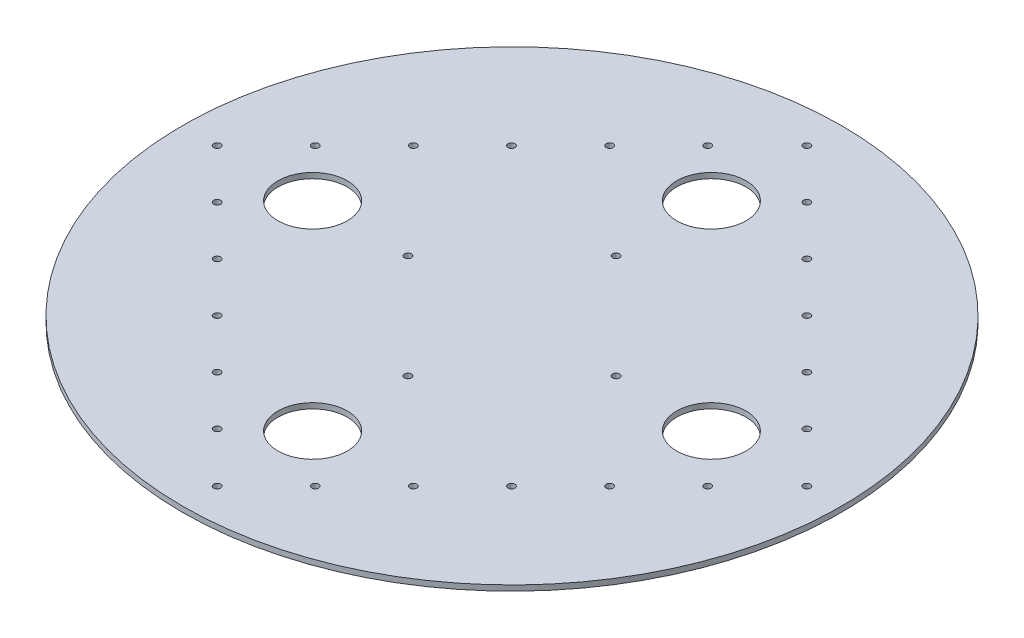
SolidWorks part; units mm, degrees
ref_plane "Front Plane" through (0, 0, 0) normal (0, 0, 1) x (1, 0, 0)
ref_plane "Top Plane" through (0, 0, 0) normal (0, 1, 0) x (1, 0, 0)
ref_plane "Right Plane" through (0, 0, 0) normal (1, 0, 0) x (0, 0, -1)
sketch "Sketch1" plane through (0, 0, 0) normal (0, 1, 0) x (1, 0, 0)
  line L0 (-170, 0) -> (0, 170) construction
  line L1 (-170, 0) -> (0, -170) construction
  circle A0 centre (0, 0) radius 190
  circle A1 centre (0, -170) radius 2
  circle A2 centre (-170, 0) radius 2
  circle A3 centre (0, 170) radius 2
  circle A4 centre (170, 0) radius 2
  circle A5 centre (-141.7157, 28.2843) radius 2
  circle A6 centre (-113.4315, 56.5685) radius 2
  circle A7 centre (-85.1472, 84.8528) radius 2
  circle A8 centre (-56.8629, 113.1371) radius 2
  circle A9 centre (-28.5786, 141.4214) radius 2
  circle A10 centre (-141.7157, -28.2843) radius 2
  circle A11 centre (28.2843, 141.7157) radius 2
  circle A12 centre (-113.4315, -56.5685) radius 2
  circle A13 centre (56.5685, 113.4315) radius 2
  circle A14 centre (-85.1472, -84.8528) radius 2
  circle A15 centre (84.8528, 85.1472) radius 2
  circle A16 centre (-56.8629, -113.1371) radius 2
  circle A17 centre (113.1371, 56.8629) radius 2
  circle A18 centre (-28.5786, -141.4214) radius 2
  circle A19 centre (141.4214, 28.5786) radius 2
  circle A20 centre (28.2843, -141.7157) radius 2
  circle A21 centre (56.5685, -113.4315) radius 2
  circle A22 centre (84.8528, -85.1472) radius 2
  circle A23 centre (113.1371, -56.8629) radius 2
  circle A24 centre (141.4214, -28.5786) radius 2
  point P14 (0, 0)
  dimension "D1" = 380
  dimension "D2" = 6
  dimension "D4" = 6
  dimension "D5" = 6
extrude "Boss-Extrude1" add sketch "Sketch1" along normal blind 3.125
sketch "Sketch2" plane through (0, 3.125, 0) normal (0, 1, 0) x (1, 0, 0)
  circle A0 centre (-60, 0) radius 2
  circle A1 centre (0, 60) radius 2
  circle A2 centre (60, 0) radius 2
  circle A3 centre (0, -60) radius 2
  point P12 (0, 0)
  dimension "D1" = 60
  dimension "D2" = 4
extrude "Cut-Extrude2" cut sketch "Sketch2" against normal up to surface (3.125 mm away) up to face at (0, 0, 190)
sketch "Sketch3" plane through (0, 3.125, 0) normal (0, 1, 0) x (1, 0, 0)
  circle A0 centre (-114.9413, 0) radius 20
  circle A1 centre (0, 114.9413) radius 20
  circle A2 centre (114.9413, 0) radius 20
  circle A3 centre (0, -114.9413) radius 20
  point P11 (0, 0)
  dimension "D1" = 4
extrude "Cut-Extrude3" cut sketch "Sketch3" against normal up to surface (3.125 mm away) up to face at (-60, 0, 2)
